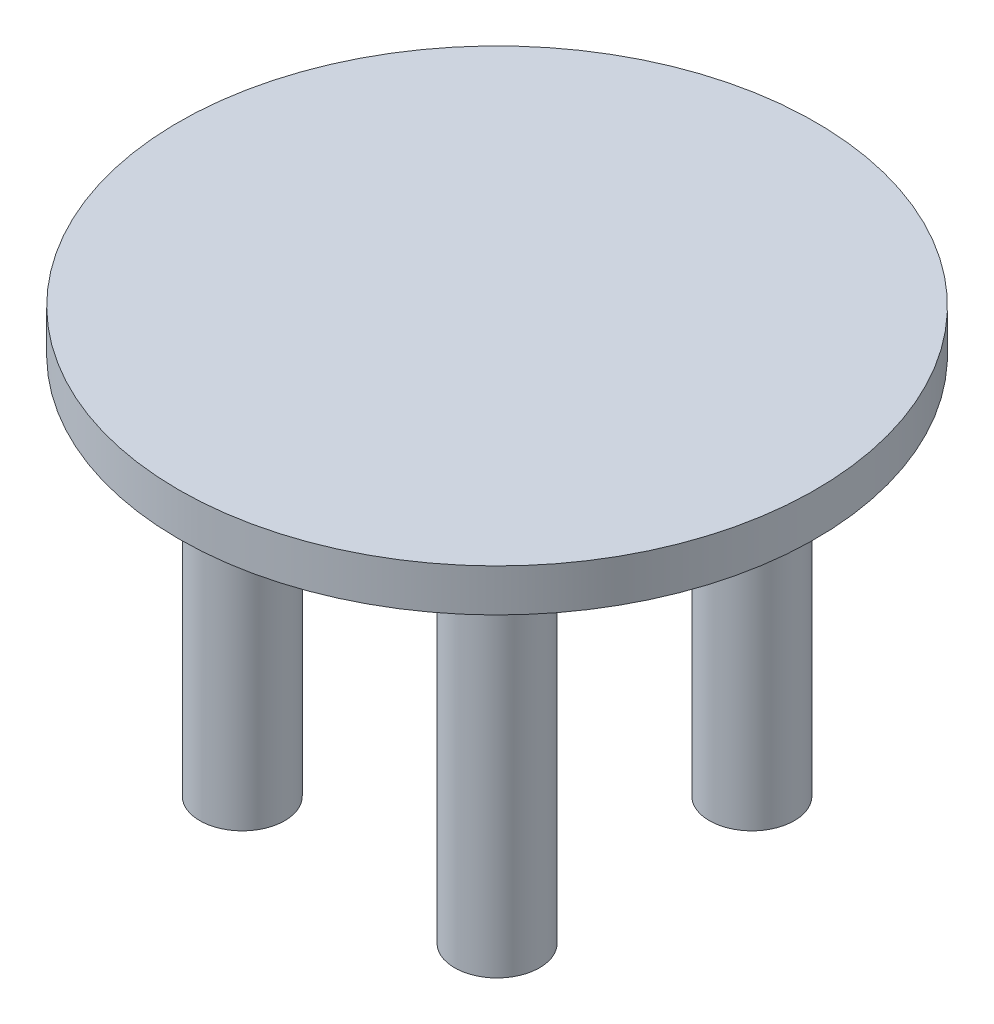
SolidWorks part; units mm, degrees
ref_plane "Front Plane" through (0, 0, 0) normal (0, 0, 1) x (1, 0, 0)
ref_plane "Top Plane" through (0, 0, 0) normal (0, 1, 0) x (1, 0, 0)
ref_plane "Right Plane" through (0, 0, 0) normal (1, 0, 0) x (0, 0, -1)
sketch "Sketch1" plane through (0, 0, 0) normal (0, 1, 0) x (1, 0, 0)
  line L0 (0, 0) -> (47.5548, 0) construction
  circle A0 centre (30, 30) radius 10
  circle A1 centre (30, -30) radius 10
  dimension "D1" = 20
  dimension "D2" = 30
  dimension "D3" = 30
extrude "Boss-Extrude1" add sketch "Sketch1" along normal blind 100
mirror "Mirror1" about plane through (0, 0, 0) normal (1, 0, 0) of bodies 102 101
sketch "Sketch2" plane through (0, 100, 0) normal (0, 1, 0) x (1, 0, 0)
  circle A0 centre (0, 0) radius 75
  dimension "D1" = 150
extrude "Boss-Extrude2" add sketch "Sketch2" against normal blind 10
